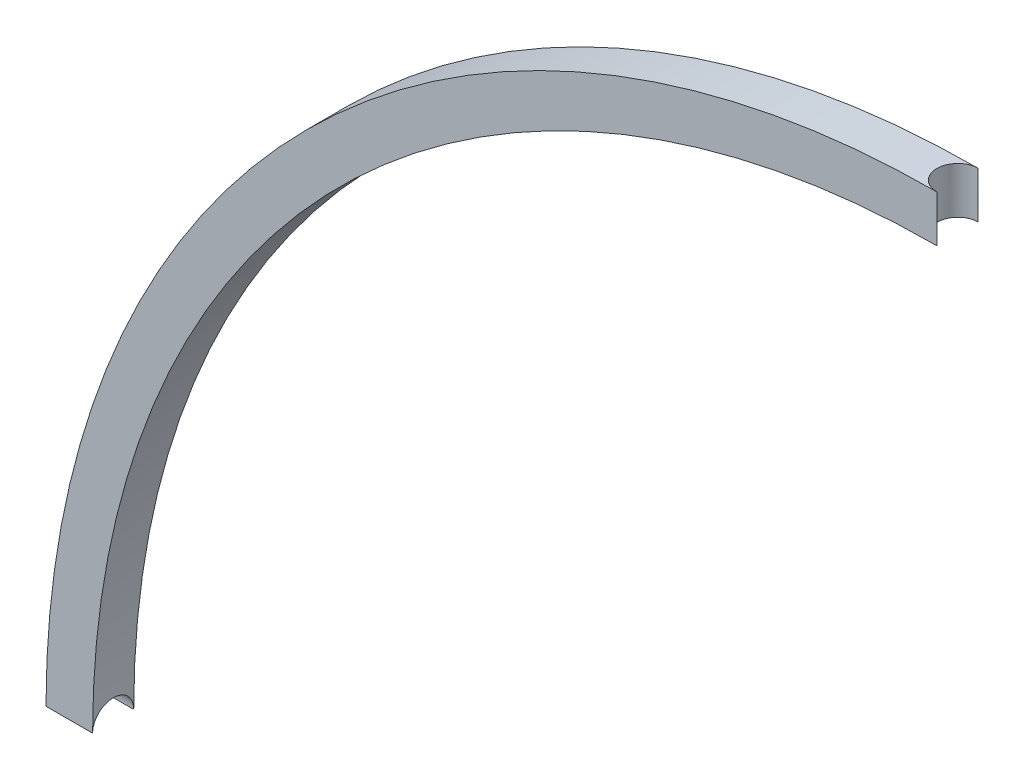
SolidWorks part; units mm, degrees
ref_plane "Front Plane" through (0, 0, 0) normal (0, 0, 1) x (1, 0, 0)
ref_plane "Top Plane" through (0, 0, 0) normal (0, 1, 0) x (1, 0, 0)
ref_plane "Right Plane" through (0, 0, 0) normal (1, 0, 0) x (0, 0, -1)
sketch "Sketch5" plane through (0, 0, 0) normal (0, 0, 1) x (1, 0, 0)
  line L0 (0, 123.2) -> (0, 130)
  line L1 (-123.2, 0) -> (-130, 0)
  arc A0 (0, 123.2) -> (-123.2, 0) centre (0, 0) ccw
  arc A1 (0, 130) -> (-130, 0) centre (0, 0) ccw
  circle A3 centre (0, 0) radius 130 construction
  circle A4 centre (0, 0) radius 123.2 construction
  point P4 (117.3864, 35.8886)
  point P5 (129.55, 0)
  dimension "D1" = 246.4
  dimension "D2" = 6.8
extrude "Boss-Extrude1" add sketch "Sketch5" along normal blind 6
sketch "Sketch6" plane through (0, 0, 0) normal (0, 1, 0) x (1, 0, 0)
  line L0 (0, -6) -> (0, 0) construction
  circle A0 centre (0, -3) radius 3
extrude "Cut-Extrude2" cut sketch "Sketch6" along normal blind 144
sketch "Sketch7" plane through (0, 0, 0) normal (1, 0, 0) x (0, 0, -1)
  line L0 (-6, 0) -> (0, 0) construction
  circle A0 centre (-3, 0) radius 3
extrude "Cut-Extrude3" cut sketch "Sketch7" against normal blind 144
